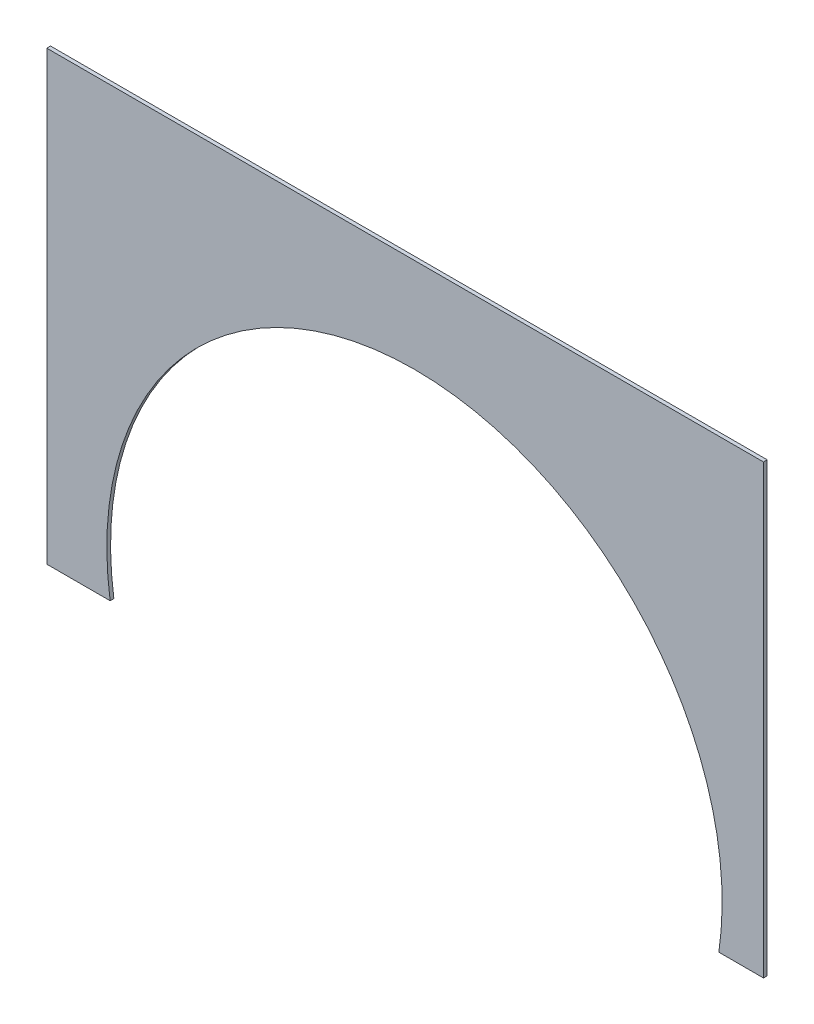
SolidWorks part; units mm, degrees
ref_plane "Спереди" through (0, 0, 0) normal (0, 0, 1) x (1, 0, 0)
ref_plane "Сверху" through (0, 0, 0) normal (0, 1, 0) x (1, 0, 0)
ref_plane "Справа" through (0, 0, 0) normal (1, 0, 0) x (0, 0, -1)
sketch "Эскиз1" plane through (0, 0, 0) normal (0, 0, 1) x (1, 0, 0)
  line L0 (2.0638, -60) -> (10.5697, -60)
  line L1 (2.0638, 0) -> (98.2879, 0)
  line L2 (2.0638, 0) -> (2.0638, -60)
  line L3 (92.2922, -60) -> (98.2879, -60)
  line L4 (98.2879, 0) -> (98.2879, -60)
  arc A0 (92.2922, -60) -> (10.5697, -60) centre (51.4309, -53.9682) ccw
extrude "Вытянуть1" add sketch "Эскиз1" along normal blind 0.5
